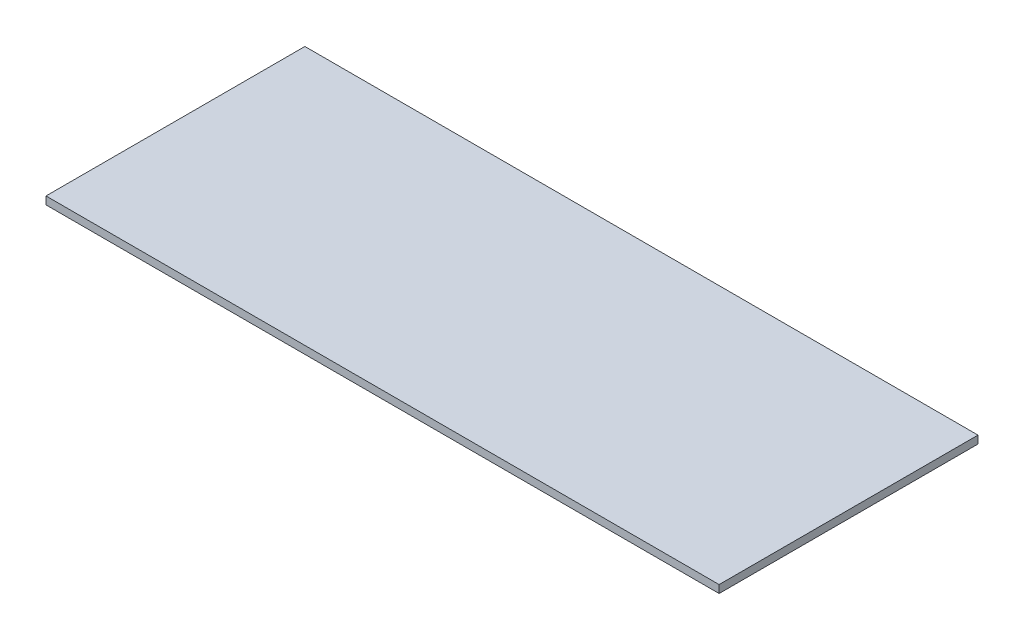
SolidWorks part; units mm, degrees
ref_plane "Plano frontal" through (0, 0, 0) normal (0, 0, 1) x (1, 0, 0)
ref_plane "Plano superior" through (0, 0, 0) normal (0, 1, 0) x (1, 0, 0)
ref_plane "Plano direito" through (0, 0, 0) normal (1, 0, 0) x (0, 0, -1)
sketch "Esboço1" plane through (0, 0, 0) normal (0, 1, 0) x (1, 0, 0)
  line L1 (650, -250) -> (-650, -250)
  line L2 (650, -250) -> (650, 250)
  line L3 (650, 250) -> (-650, 250)
  line L4 (-650, -250) -> (-650, 250)
  line L5 (650, -250) -> (-650, 250) construction
  line L6 (650, 250) -> (-650, -250) construction
  point P0 (0, 0)
  dimension "D1" = 1300
  dimension "D2" = 500
extrude "Ressalto-extrusão1" add sketch "Esboço1" along normal blind 15
